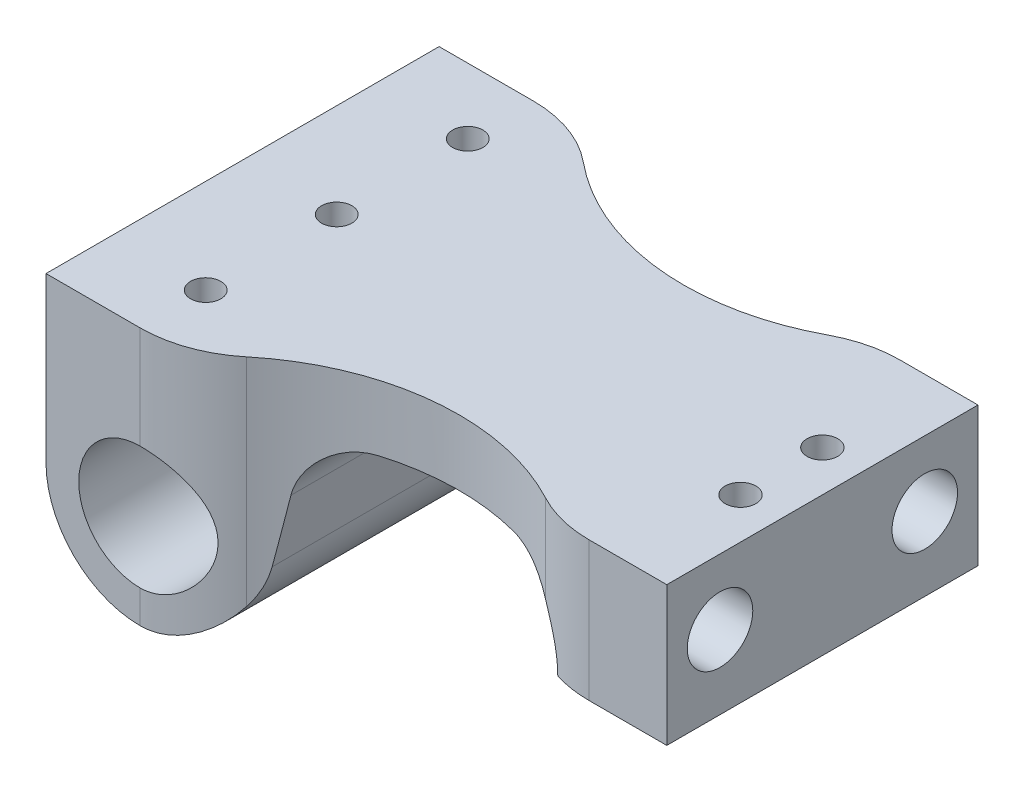
SolidWorks part; units mm, degrees
ref_plane "Front Plane" through (0, 0, 0) normal (0, 0, 1) x (1, 0, 0)
ref_plane "Top Plane" through (0, 0, 0) normal (0, 1, 0) x (1, 0, 0)
ref_plane "Right Plane" through (0, 0, 0) normal (1, 0, 0) x (0, 0, -1)
sketch "Sketch1" plane through (0, 0, 0) normal (0, 0, 1) x (1, 0, 0)
  line L0 (-17.4747, 5.003) -> (-16.0995, 12.8024)
  line L1 (10, -10) -> (-10, -10) construction
  line L2 (10, -10) -> (10, 10) construction
  line L3 (10, 10) -> (-10, 10) construction
  line L4 (-10, -10) -> (-10, 10) construction
  line L5 (10, -10) -> (-10, 10) construction
  line L6 (10, 10) -> (-10, -10) construction
  line L7 (10, 10) -> (20, 10) construction
  line L8 (10, 10) -> (10, -10) construction
  line L9 (10, -10) -> (20, -10) construction
  line L10 (20, 10) -> (20, -10) construction
  line L11 (-10, 10) -> (10, 10) construction
  line L12 (-10, 10) -> (-10, 19) construction
  line L13 (-10, 19) -> (10, 19) construction
  line L14 (10, 10) -> (10, 19) construction
  line L15 (-10, 10) -> (10, 10) construction
  line L16 (-10, 10) -> (-10, 15) construction
  line L17 (-10, 15) -> (10, 15) construction
  line L18 (10, 10) -> (10, 15) construction
  line L19 (16.5, 14.5) -> (36.5, 14.5) construction
  line L20 (16.5, 14.5) -> (16.5, 10) construction
  line L21 (25, -0.5) -> (36.5, -0.5) construction
  line L22 (36.5, 14.5) -> (36.5, -0.5) construction
  line L23 (-40.3, 27) -> (12.6275, 27)
  line L24 (-40.3, 27) -> (-40.3, 7)
  line L25 (-8.7134, 19) -> (7.5, 19)
  line L28 (25, 10) -> (25, 27)
  line L29 (25, 27) -> (12.6275, 27)
  line L30 (16.5, 10) -> (25, 10)
  line L31 (-10, 15) -> (-15, 15) construction
  line L32 (-10, 15) -> (-10, -4.1558) construction
  line L33 (-10, -4.1558) -> (-15, -4.1558) construction
  line L34 (-15, 15) -> (-15, -4.1558) construction
  circle A0 centre (-28.8, 7) radius 7.5
  arc A1 (-40.3, 7) -> (-17.4747, 5.003) centre (-28.8, 7) ccw
  arc A2 (-16.0995, 12.8024) -> (-8.7134, 19) centre (-8.7134, 11.5) cw
  arc A3 (7.5, 19) -> (16.5, 10) centre (7.5, 10) cw
  point P3 (0, 0)
  dimension "D1" = 15
  dimension "D2" = 4
  dimension "D5" = 18.8
  dimension "D6" = 3
  dimension "D10" = 6.5
  dimension "D13" = 7.5
  dimension "D3" = 20
  dimension "D4" = 20
  dimension "D7" = 10
  dimension "D8" = 9
  dimension "D9" = 5
  dimension "D11" = 20
  dimension "D12" = 8
  dimension "D14" = 80
  dimension "D15" = 5
  dimension "D16" = 5
extrude "Boss-Extrude1" add sketch "Sketch1" along normal mid plane 48
sketch "Sketch2" plane through (25, 0, 0) normal (1, 0, 0) x (0, 0, -1)
  line L0 (-12.5, 19) -> (0, 0) construction
  line L1 (0, 0) -> (12.5, 19) construction
  line L3 (-24, 27) -> (24, 27) construction
  circle A0 centre (-12.5, 19) radius 4
  circle A1 centre (12.5, 19) radius 4
  dimension "D1" = 8
  dimension "D2" = 25
  dimension "D3" = 8
extrude "Cut-Extrude1" cut sketch "Sketch2" against normal blind 5
sketch "Sketch3" plane through (0, 27, 0) normal (0, 1, 0) x (1, 0, 0)
  line L0 (25, -24) -> (-40.3, -24) construction
  line L1 (-28.8, -24) -> (25, -24)
  line L2 (25, -24) -> (25, -19)
  line L3 (21, -19) -> (25, -19)
  line L4 (25, -24) -> (25, 24) construction
  line L5 (-36.3, -24) -> (-21.3, -24) construction
  line L6 (0, 0) -> (25, 0) construction
  line L7 (21, 19) -> (25, 19)
  line L8 (25, 24) -> (25, 19)
  line L9 (-28.8, 24) -> (25, 24)
  arc A0 (-19.2546, -20.5709) -> (13.9454, -17.2375) centre (-0.1638, -43.7126) cw
  arc A1 (-28.8, -24) -> (-19.2546, -20.5709) centre (-28.8, -9) ccw
  arc A2 (13.9454, -17.2375) -> (21, -19) centre (21, -4) ccw
  arc A3 (13.9454, 17.2375) -> (21, 19) centre (21, 4) cw
  arc A4 (-28.8, 24) -> (-19.2546, 20.5709) centre (-28.8, 9) cw
  arc A5 (-19.2546, 20.5709) -> (13.9454, 17.2375) centre (-0.1638, 43.7126) ccw
  dimension "D2" = 15
  dimension "D3" = 30
  dimension "D4" = 15
  dimension "D1" = 5
  dimension "D5" = 4
extrude "Cut-Extrude2" cut sketch "Sketch3" against normal through all both and the other way through all
sketch "Sketch4" plane through (25, 0, 0) normal (1, 0, 0) x (0, 0, -1)
  line L1 (-19, 27) -> (19, 27)
  line L2 (-19, 27) -> (-19, 10)
  line L3 (-19, 10) -> (19, 10)
  line L4 (19, 27) -> (19, 10)
  circle A0 centre (12.5, 19) radius 4 construction
  circle A1 centre (-12.5, 19) radius 4 construction
  circle A2 centre (12.5, 19) radius 4
  circle A3 centre (-12.5, 19) radius 4
extrude "Boss-Extrude2" add sketch "Sketch4" along normal blind 5.5
sketch "Sketch5" plane through (0, 27, 0) normal (0, 1, 0) x (1, 0, 0)
  line L0 (30.5, 19) -> (25.5, 5) construction
  line L1 (25.5, 5) -> (25.5, -5) construction
  line L2 (25.5, -5) -> (30.5, -19) construction
  line L3 (30.5, 19) -> (30.5, -19) construction
  circle A0 centre (25.5, -5) radius 1.875
  circle A1 centre (25.5, 5) radius 1.875
  dimension "D1" = 3.75
  dimension "D2" = 3.75
  dimension "D3" = 10
  dimension "D4" = 5
extrude "Cut-Extrude3" cut sketch "Sketch5" against normal through all both and the other way through all
sketch "Sketch6" plane through (0, 27, 0) normal (0, 1, 0) x (1, 0, 0)
  line L0 (-28.8, -24) -> (-28.8, 24) construction
  line L1 (-28.8, 16) -> (-40.3, 24) construction
  line L2 (-40.3, 24) -> (-40.3, -24) construction
  line L3 (-40.3, -24) -> (-28.8, -16) construction
  line L4 (-28.8, 24) -> (-40.3, 24) construction
  circle A0 centre (-28.8, 16) radius 1.85
  circle A1 centre (-28.8, 0) radius 1.85
  circle A2 centre (-28.8, -16) radius 1.85
  arc A3 (-28.8, -24) -> (-19.2546, -20.5709) centre (-28.8, -9) ccw construction
  point P13 (0, 0)
  point P15 (0, 0)
  dimension "D1" = 3.7
  dimension "D2" = 8
extrude "Cut-Extrude4" cut sketch "Sketch6" against normal blind 9
